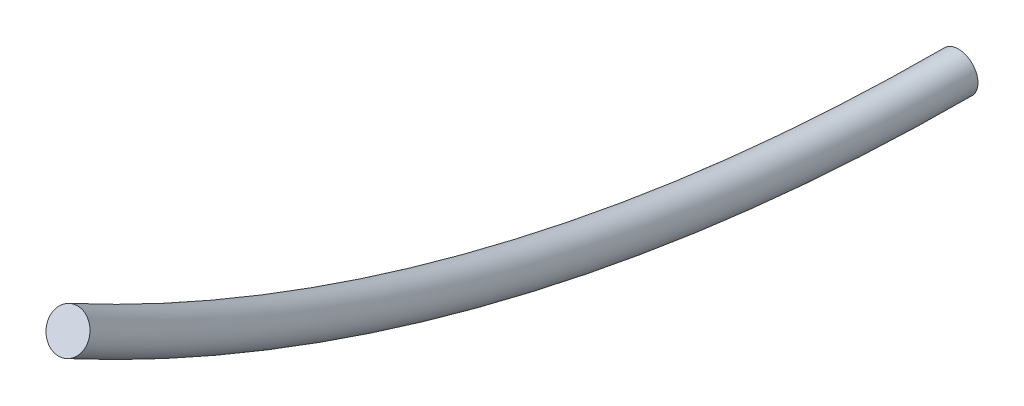
SolidWorks part; units mm, degrees
ref_plane "Front" through (0, 0, 0) normal (0, 0, 1) x (1, 0, 0)
ref_plane "Top" through (0, 0, 0) normal (0, 1, 0) x (1, 0, 0)
ref_plane "Right" through (0, 0, 0) normal (1, 0, 0) x (0, 0, -1)
sketch "Sketch1" plane through (25457.3894, 23216.3742, 0) normal (0, 0, -1) x (-0.5236, 0.852, 0)
  circle A0 centre (-19122.9134, -38499.2122) radius 50.8
  circle A2 centre (-19122.9134, -38499.2122) radius 50.8 construction
ref_plane "Plane1" through (3213.9839, -133.2791, 0) normal (-0.9991, 0.0414, 0) x (-0.0412, -0.9934, 0.1067)
sketch "Sketch2" plane through (3213.9839, -133.2791, 0) normal (-0.9991, 0.0414, 0) x (-0.0412, -0.9934, 0.1067)
  line L0 (12691.9328, 988.5791) -> (12071.3055, 2480.8124) construction
  line L1 (13037.2469, -1399.5544) -> (13291.5326, 969.1888) construction
  line L2 (13037.2469, -1399.5544) -> (12691.9328, 988.5791) construction
  line L3 (13014.9589, -183.7449) -> (12864.5899, -205.4877) construction
  arc A0 (13037.2469, -1399.5544) -> (12691.9328, 988.5791) centre (8198.7857, -880.1434) ccw
  point P3 (12770.3933, 787.4594)
  point P5 (12984.0139, 4.2126)
  point P6 (13064.4453, -803.6489)
  dimension "D1" = 2438.4
  dimension "D5" = 151.9328
  dimension "D3" = 812.8
  dimension "D2" = 215.9
  dimension "D4" = 812.8
sweep "Sweep1" add profiles "Sketch1" path "Sketch2"
